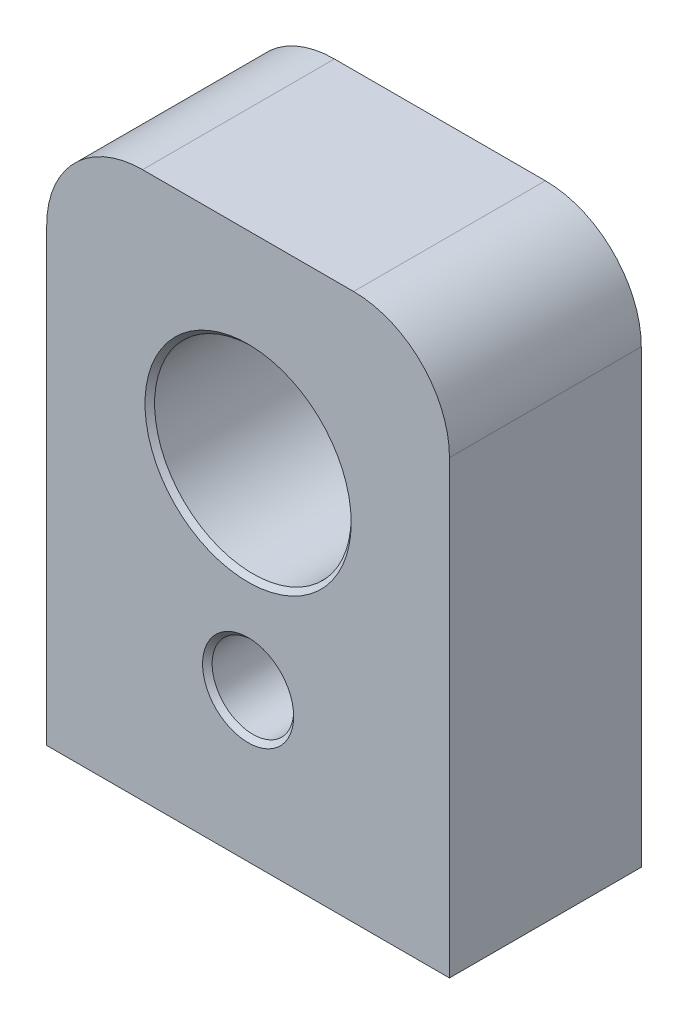
SolidWorks part; units mm, degrees
ref_plane "Front Plane" through (0, 0, 0) normal (0, 0, 1) x (1, 0, 0)
ref_plane "Top Plane" through (0, 0, 0) normal (0, 1, 0) x (1, 0, 0)
ref_plane "Right Plane" through (0, 0, 0) normal (1, 0, 0) x (0, 0, -1)
sketch "Sketch1" plane through (0, 0, 0) normal (0, 0, 1) x (1, 0, 0)
  line L1 (-33.4449, -26.5193) -> (-3.4449, -26.5193) construction
  line L2 (-39.4449, 30.4807) -> (-39.4449, -10.5193) construction
  line L3 (2.5551, -20.5193) -> (2.5551, 30.4807) construction
  line L4 (2.5551, 30.4807) -> (-39.4449, 30.4807) construction
  line L8 (-7.4449, 30.4807) -> (-29.4449, 30.4807)
  line L9 (-39.4449, 20.4807) -> (-39.4449, -26.5193)
  line L10 (-39.4449, -26.5193) -> (2.5551, -26.5193)
  line L11 (2.5551, -26.5193) -> (2.5551, 20.4807)
  circle A0 centre (-18.4449, 9.4807) radius 10.25
  circle A1 centre (-18.4449, -11.0193) radius 4.25
  arc A2 (2.5551, 20.4807) -> (-7.4449, 30.4807) centre (-7.4449, 20.4807) ccw
  arc A3 (-39.4449, 20.4807) -> (-29.4449, 30.4807) centre (-29.4449, 20.4807) cw
  dimension "D2" = 10
  dimension "D1" = 8.5
  dimension "D3" = 20.5
extrude "Boss-Extrude1" add sketch "Sketch1" against normal mid plane 20
chamfer "Chamfer1" distance 0.5 angle 45 2 edges at (-8.1949, 9.4807, 10) (-8.1949, 9.4807, -10)
chamfer "Chamfer2" distance 0.5 angle 45 2 edges at (-14.1949, -11.0193, 10) (-14.1949, -11.0193, -10)
